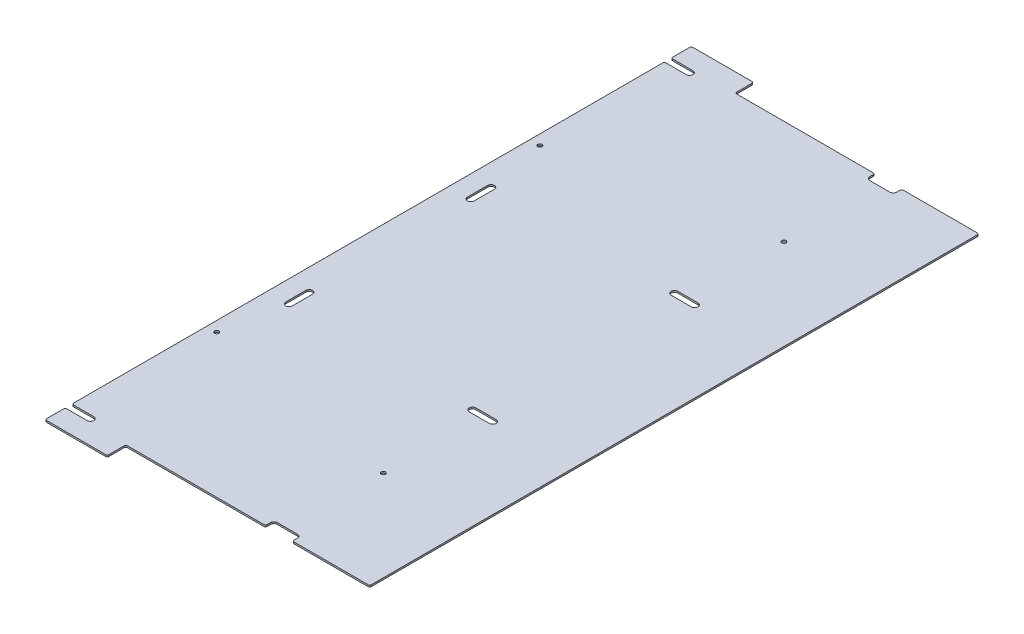
SolidWorks part; units mm, degrees
material "PC High Viscosity"
ref_plane "Front Plane" through (0, 0, 0) normal (0, 0, 1) x (1, 0, 0)
ref_plane "Top Plane" through (0, 0, 0) normal (0, 1, 0) x (1, 0, 0)
ref_plane "Right Plane" through (0, 0, 0) normal (1, 0, 0) x (0, 0, -1)
sketch "Sketch1" plane through (0, 0, 0) normal (0, 1, 0) x (1, 0, 0)
  line L1 (0, 0) -> (609.6, 0)
  line L2 (0, 0) -> (0, 1219.2)
  line L3 (0, 1219.2) -> (609.6, 1219.2)
  line L4 (609.6, 0) -> (609.6, 1219.2)
  dimension "D1" = 609.6
  dimension "D2" = 1219.2
extrude "Boss-Extrude1" add sketch "Sketch1" along normal blind 3.175
hole_wizard "5/16 (0.3125) Diameter Hole1" positions "Sketch3" profile "Sketch4" hole size "5/16" standard "ANSI Inch" end condition up to next
sketch "Sketch3" plane through (0, 3.175, 0) normal (0, 1, 0) x (1, 0, 0)
  line L0 (609.6, 609.6) -> (0, 609.6) construction
  line L1 (609.6, 0) -> (609.6, 1219.2) construction
  line L2 (0, 1219.2) -> (0, 0) construction
  line L3 (609.6, 1219.2) -> (0, 1219.2) construction
  line L4 (1219.2, 1219.2) -> (1219.2, 0) construction
  line L5 (0, 0) -> (609.6, 0) construction
  point P0 (50.8, 914.4)
  point P10 (50.8, 304.8)
  point P11 (438.15, 987.425)
  point P16 (438.15, 231.775)
  dimension "D1" = 781.05
  dimension "D2" = 1168.4
  dimension "D3" = 304.8
  dimension "D4" = 377.825
  dimension "D5" = 609.6
sketch "Sketch4" plane through (50.8, 3.175, -914.4) normal (1, 0, 0) x (0, 0, 1)
  line L0 (0, 0) -> (0, 3.175)
  line L1 (0, 3.175) -> (3.9688, 3.175)
  line L2 (3.9688, 3.175) -> (3.9687, 0)
  line L5 (3.9687, 0) -> (0, 0)
  line L11 (0, -6.35) -> (0, 107.95) construction
  dimension "Thru Hole Dia." = 7.9375
  dimension "Thru Hole Depth" = 3.175
sketch "Sketch5" plane through (0, 3.175, 0) normal (0, 1, 0) x (1, 0, 0)
  line L0 (1219.2, 1219.2) -> (1219.2, 0) construction
  line L1 (149.225, 1219.2) -> (149.225, 1184.275)
  line L2 (1066.8, 1219.2) -> (152.4, 1219.2) construction
  line L3 (1066.8, 1219.2) -> (1066.8, 1187.45) construction
  line L4 (609.6, 1219.2) -> (0, 1219.2)
  line L5 (0, 1219.2) -> (0, 0)
  line L6 (0, 0) -> (609.6, 0)
  line L7 (609.6, 0) -> (609.6, 1219.2)
  line L8 (1219.2, 1219.2) -> (0, 1219.2) construction
  line L10 (0, 0) -> (1219.2, 0) construction
  line L11 (609.6, 0) -> (609.6, 1219.2) construction
  line L12 (1066.8, 1187.45) -> (152.4, 1187.45) construction
  line L13 (152.4, 1219.2) -> (152.4, 1187.45) construction
  line L14 (1069.975, 1184.275) -> (149.225, 1184.275)
  line L15 (1069.975, 1219.2) -> (1069.975, 1184.275)
  line L16 (149.225, 1219.2) -> (1069.975, 1219.2)
  line L17 (0, 1219.2) -> (0, 0) construction
  line L18 (1219.2, 609.6) -> (0, 609.6) construction
  line L19 (149.225, 0) -> (149.225, 34.925)
  line L20 (1069.975, 0) -> (1069.975, 34.925)
  line L21 (1069.975, 34.925) -> (149.225, 34.925)
  line L22 (149.225, 0) -> (1069.975, 0)
  circle A0 centre (438.15, 987.425) radius 3.9688 construction
  dimension "D5" = 192.8813
  dimension "D2" = 914.4
  dimension "D3" = 31.75
  dimension "D1" = 0
  dimension "D4" = 3.175
extrude "Cut-Extrude2" cut sketch "Sketch5" against normal through all
sketch "Sketch2" plane through (0, 3.175, 0) normal (0, 1, 0) x (1, 0, 0)
  line L5 (0, 0) -> (0, 1219.2)
  line L6 (0, 1219.2) -> (0, 0) construction
  line L7 (0, 1219.2) -> (31.75, 1219.2)
  line L8 (149.225, 1219.2) -> (0, 1219.2) construction
  line L9 (31.75, 1219.2) -> (31.75, 812.8)
  line L10 (0, 609.6) -> (31.75, 609.6) construction
  line L11 (31.75, 406.4) -> (31.75, 812.8)
  line L12 (31.75, 0) -> (31.75, 406.4)
  line L13 (0, 0) -> (31.75, 0)
  dimension "D1" = 31.75
extrude "Cut-Extrude1" cut sketch "Sketch2" against normal through all
sketch "Sketch6" plane through (0, 0, 0) normal (0, -1, 0) x (1, 0, 0)
  line L0 (149.225, -1184.275) -> (609.6, -1184.275) construction
  line L1 (609.6, -34.925) -> (609.346, -34.925)
  line L2 (609.6, -34.925) -> (609.6, -1184.275)
  line L3 (609.6, -1184.275) -> (609.346, -1184.275)
  line L4 (609.346, -34.925) -> (609.346, -1184.275)
  dimension "D1" = 0.254
extrude "Cut-Extrude3" cut sketch "Sketch6" against normal through all
sketch "Sketch7" plane through (0, 3.175, 0) normal (0, 1, 0) x (1, 0, 0)
  line L0 (609.346, 34.925) -> (609.346, 1184.275) construction
  line L1 (28.575, 1219.2) -> (609.346, 1219.2)
  line L2 (28.575, 1219.2) -> (28.575, 1174.75)
  line L3 (28.575, 1174.75) -> (609.346, 1174.75)
  line L4 (609.346, 1219.2) -> (609.346, 1174.75)
  line L5 (438.15, 44.45) -> (438.15, 419.1) construction
  line L6 (28.575, 1174.75) -> (73.025, 1174.75)
  line L7 (28.575, 1174.75) -> (28.575, 44.45)
  line L8 (28.575, 44.45) -> (73.025, 44.45)
  line L9 (73.025, 1174.75) -> (73.025, 44.45)
  line L10 (28.575, 0) -> (609.346, 0)
  line L11 (28.575, 0) -> (28.575, 44.45)
  line L12 (28.575, 44.45) -> (609.346, 44.45)
  line L13 (609.346, 0) -> (609.346, 44.45)
  line L14 (73.025, 800.1) -> (609.346, 800.1)
  line L15 (73.025, 800.1) -> (73.025, 762)
  line L16 (73.025, 762) -> (609.346, 762)
  line L17 (609.346, 800.1) -> (609.346, 762)
  line L18 (73.025, 457.2) -> (609.346, 457.2)
  line L19 (73.025, 457.2) -> (73.025, 419.1)
  line L20 (73.025, 419.1) -> (609.346, 419.1)
  line L21 (609.346, 457.2) -> (609.346, 419.1)
  line L22 (419.1, 1174.75) -> (457.2, 1174.75)
  line L23 (419.1, 1174.75) -> (419.1, 800.1)
  line L24 (419.1, 800.1) -> (457.2, 800.1)
  line L25 (457.2, 1174.75) -> (457.2, 800.1)
  line L26 (419.1, 419.1) -> (457.2, 419.1)
  line L27 (419.1, 419.1) -> (419.1, 44.45)
  line L28 (419.1, 44.45) -> (457.2, 44.45)
  line L29 (457.2, 419.1) -> (457.2, 44.45)
  line L30 (609.346, 609.6) -> (28.575, 609.6) construction
  line L31 (149.225, 1219.2) -> (31.75, 1219.2) construction
  line L32 (31.75, 0) -> (31.75, 1219.2) construction
  circle A0 centre (438.15, 231.775) radius 3.9688 construction
  circle A1 centre (438.15, 231.775) radius 3.9688 construction
  dimension "D1" = 44.45
  dimension "D2" = 38.1
  dimension "D3" = 304.8
  dimension "D4" = 3.175
sketch "Sketch13" plane through (0, 3.175, 0) normal (0, 1, 0) x (1, 0, 0)
  line L0 (73.025, 419.1) -> (73.025, 457.2) construction
  line L1 (66.675, 419.1) -> (66.675, 457.2)
  line L2 (79.375, 419.1) -> (79.375, 457.2)
  line L3 (419.1, 419.1) -> (457.2, 419.1) construction
  line L4 (419.1, 425.45) -> (457.2, 425.45)
  line L5 (419.1, 412.75) -> (457.2, 412.75)
  line L6 (28.575, 44.45) -> (73.025, 44.45) construction
  line L7 (28.575, 50.8) -> (73.025, 50.8)
  line L8 (28.575, 38.1) -> (73.025, 38.1)
  line L9 (419.1, 44.45) -> (457.2, 44.45) construction
  line L10 (419.1, 50.8) -> (457.2, 50.8)
  line L11 (419.1, 38.1) -> (457.2, 38.1)
  line L12 (609.346, 609.6) -> (28.575, 609.6) construction
  line L13 (73.025, 800.1) -> (73.025, 762) construction
  line L14 (66.675, 800.1) -> (66.675, 762)
  line L15 (79.375, 800.1) -> (79.375, 762)
  line L16 (419.1, 800.1) -> (457.2, 800.1) construction
  line L17 (419.1, 793.75) -> (457.2, 793.75)
  line L18 (419.1, 806.45) -> (457.2, 806.45)
  line L19 (28.575, 1174.75) -> (73.025, 1174.75) construction
  line L20 (28.575, 1168.4) -> (73.025, 1168.4)
  line L21 (28.575, 1181.1) -> (73.025, 1181.1)
  line L22 (419.1, 1174.75) -> (457.2, 1174.75) construction
  line L23 (419.1, 1168.4) -> (457.2, 1168.4)
  line L24 (419.1, 1181.1) -> (457.2, 1181.1)
  arc A0 (66.675, 419.1) -> (79.375, 419.1) centre (73.025, 419.1) ccw
  arc A1 (79.375, 457.2) -> (66.675, 457.2) centre (73.025, 457.2) ccw
  arc A2 (419.1, 425.45) -> (419.1, 412.75) centre (419.1, 419.1) ccw
  arc A3 (457.2, 412.75) -> (457.2, 425.45) centre (457.2, 419.1) ccw
  arc A4 (28.575, 50.8) -> (28.575, 38.1) centre (28.575, 44.45) ccw
  arc A5 (73.025, 38.1) -> (73.025, 50.8) centre (73.025, 44.45) ccw
  arc A6 (419.1, 50.8) -> (419.1, 38.1) centre (419.1, 44.45) ccw
  arc A7 (457.2, 38.1) -> (457.2, 50.8) centre (457.2, 44.45) ccw
  arc A8 (66.675, 800.1) -> (79.375, 800.1) centre (73.025, 800.1) cw
  arc A9 (79.375, 762) -> (66.675, 762) centre (73.025, 762) cw
  arc A10 (419.1, 793.75) -> (419.1, 806.45) centre (419.1, 800.1) cw
  arc A11 (457.2, 806.45) -> (457.2, 793.75) centre (457.2, 800.1) cw
  arc A12 (28.575, 1168.4) -> (28.575, 1181.1) centre (28.575, 1174.75) cw
  arc A13 (73.025, 1181.1) -> (73.025, 1168.4) centre (73.025, 1174.75) cw
  arc A14 (419.1, 1168.4) -> (419.1, 1181.1) centre (419.1, 1174.75) cw
  arc A15 (457.2, 1181.1) -> (457.2, 1168.4) centre (457.2, 1174.75) cw
  point P4 (73.025, 438.15)
  point P9 (438.15, 419.1)
  point P18 (50.8, 44.45)
  point P27 (438.15, 44.45)
  point P42 (73.025, 781.05)
  point P49 (438.15, 800.1)
  point P56 (50.8, 1174.75)
  point P63 (438.15, 1174.75)
  dimension "D1" = 6.35
extrude "Cut-Extrude4" cut sketch "Sketch13" against normal through all
sketch "Sketch14" plane through (0, 3.175, 0) normal (0, 1, 0) x (1, 0, 0)
  line L0 (412.75, 44.45) -> (412.75, 34.925)
  line L1 (609.346, 34.925) -> (149.225, 34.925) construction
  line L2 (412.75, 34.925) -> (463.55, 34.925)
  line L3 (463.55, 34.925) -> (463.55, 44.45)
  line L4 (463.55, 44.45) -> (412.75, 44.45)
  line L5 (609.346, 609.6) -> (28.575, 609.6) construction
  line L6 (609.346, 34.925) -> (609.346, 1184.275) construction
  line L7 (463.55, 1174.75) -> (412.75, 1174.75)
  line L8 (463.55, 1184.275) -> (463.55, 1174.75)
  line L9 (412.75, 1184.275) -> (463.55, 1184.275)
  line L10 (412.75, 1174.75) -> (412.75, 1184.275)
  arc A0 (419.1, 50.8) -> (419.1, 38.1) centre (419.1, 44.45) ccw construction
  arc A1 (457.2, 38.1) -> (457.2, 50.8) centre (457.2, 44.45) ccw construction
extrude "Cut-Extrude5" cut sketch "Sketch14" against normal through all
fillet "Fillet1" radius 3.175 16 edges at (31.75, 1.5875, 0) (149.225, 1.5875, 0) (149.225, 1.5875, -1184.275) (149.225, 1.5875, -1219.2) (31.75, 1.5875, -1219.2) (149.225, 1.5875, -34.925) (609.346, 1.5875, -34.925) (609.346, 1.5875, -1184.275) (463.55, 1.5875, -34.925) (463.55, 1.5875, -1184.275) (412.75, 1.5875, -1184.275) (31.75, 1.5875, -1181.1) (31.75, 1.5875, -1168.4) (31.75, 1.5875, -38.1) (412.75, 1.5875, -34.925) (31.75, 1.5875, -50.8)
